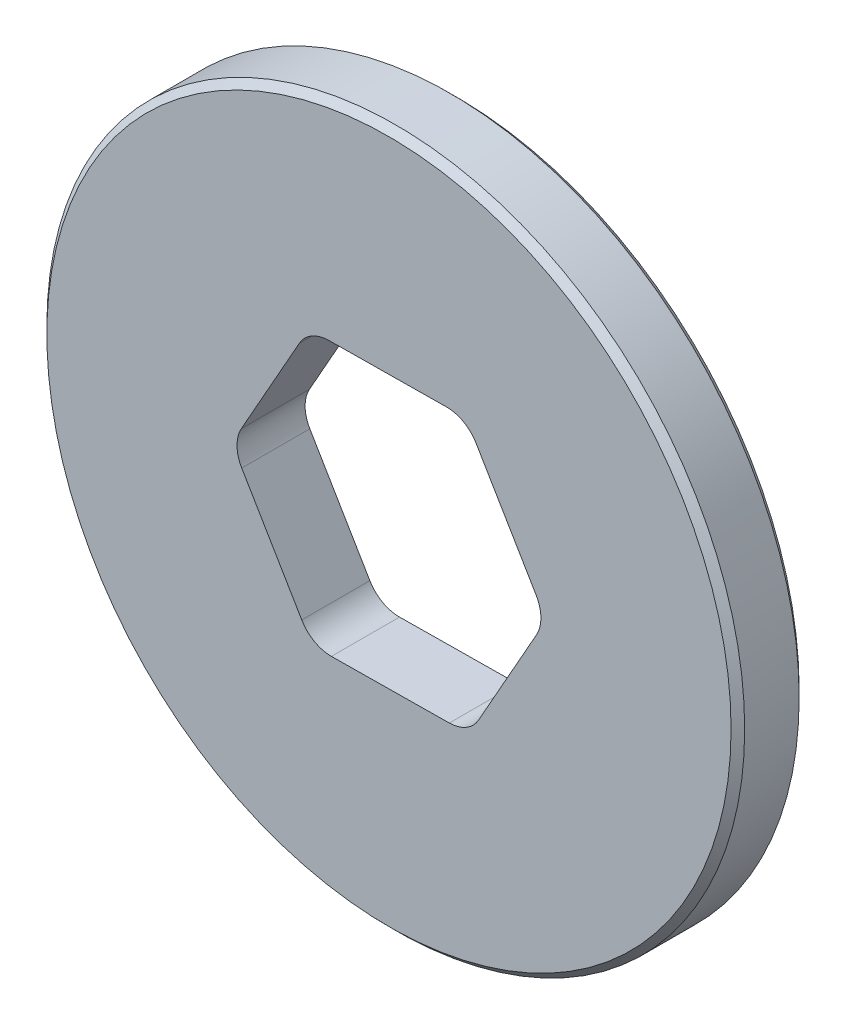
SolidWorks part; units mm, degrees
ref_plane "Front Plane" through (0, 0, 0) normal (0, 0, 1) x (1, 0, 0)
ref_plane "Top Plane" through (0, 0, 0) normal (0, 1, 0) x (1, 0, 0)
ref_plane "Right Plane" through (0, 0, 0) normal (1, 0, 0) x (0, 0, -1)
sketch "Sketch1" plane through (0, 0, 0) normal (0, 0, 1) x (1, 0, 0)
  line L1 (23.5104, -39.7567) -> (46.1855, 0.4823)
  line L2 (46.1855, 0.4823) -> (22.6751, 40.239)
  line L3 (22.6751, 40.239) -> (-23.5104, 39.7567)
  line L4 (-23.5104, 39.7567) -> (-46.1855, -0.4823)
  line L5 (-46.1855, -0.4823) -> (-22.6751, -40.239)
  line L6 (-22.6751, -40.239) -> (23.5104, -39.7567)
  circle A0 centre (0, 0) radius 102.5
  circle A1 centre (0, 0) radius 40 construction
  dimension "D1" = 205
  dimension "D2" = 80
extrude "Boss-Extrude1" add sketch "Sketch1" along normal blind 20
fillet "Fillet1" radius 10 6 edges at (23.5104, -39.7567, 10) (-22.6751, -40.239, 10) (46.1855, 0.4823, 10) (22.6751, 40.239, 10) (-23.5104, 39.7567, 10) (-46.1855, -0.4823, 10)
chamfer "Chamfer1" distance 2 angle 45 2 edges at (102.5, 0, 0) (102.5, 0, 20)
